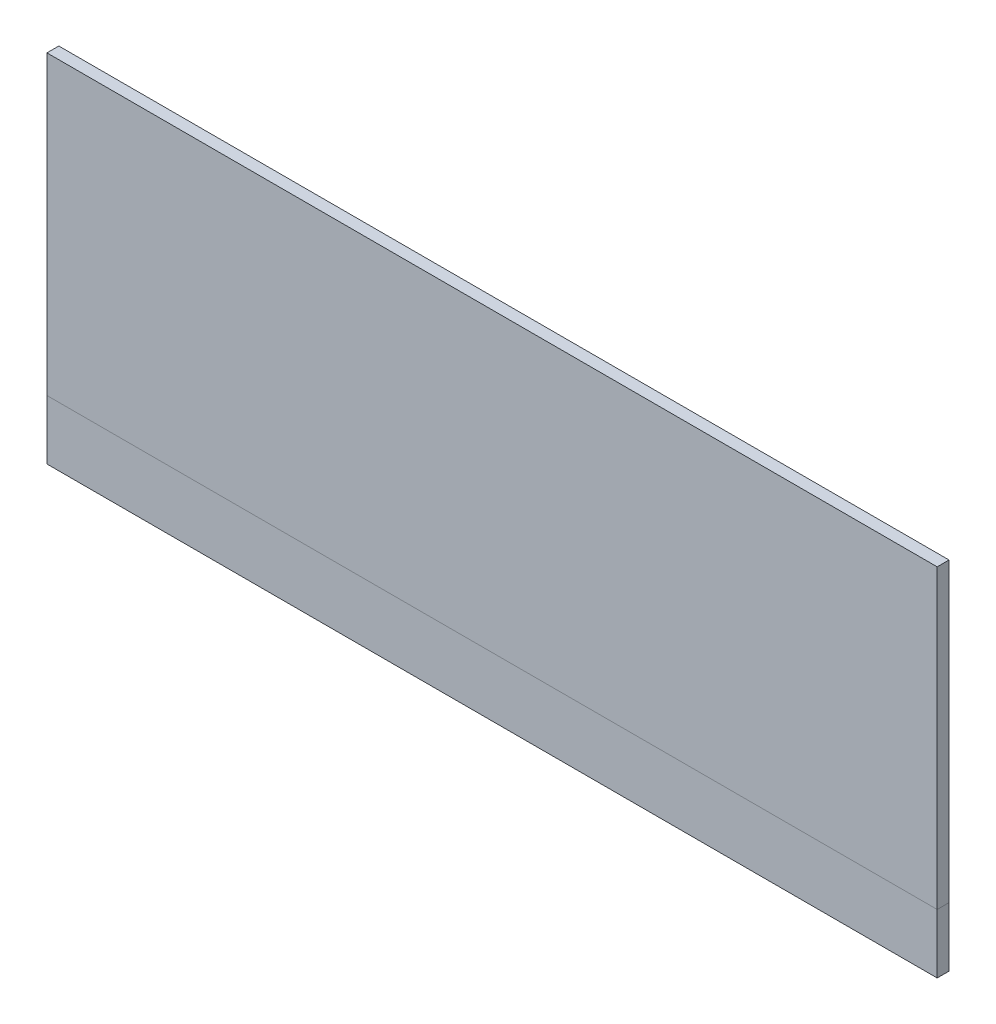
SolidWorks part; units mm, degrees
ref_plane "Front Plane" through (0, 0, 0) normal (0, 0, 1) x (1, 0, 0)
ref_plane "Top Plane" through (0, 0, 0) normal (0, 1, 0) x (1, 0, 0)
ref_plane "Right Plane" through (0, 0, 0) normal (1, 0, 0) x (0, 0, -1)
sketch "Sketch1" plane through (0, 0, 0) normal (0, 0, 1) x (1, 0, 0)
  line L1 (-187.5, 62.5) -> (187.5, 62.5)
  line L2 (-187.5, 62.5) -> (-187.5, -62.5)
  line L3 (-187.5, -62.5) -> (187.5, -62.5)
  line L4 (187.5, 62.5) -> (187.5, -62.5)
  line L5 (-187.5, 62.5) -> (187.5, -62.5) construction
  line L6 (-187.5, -62.5) -> (187.5, 62.5) construction
  point P0 (0, 0)
  dimension "D1" = 125
  dimension "D2" = 375
extrude "Boss-Extrude1" add sketch "Sketch1" along normal blind 5
sketch "Sketch2" plane through (0, 0, 5) normal (0, 0, 1) x (1, 0, 0)
  line L1 (-187.5, -62.5) -> (187.5, -62.5)
  line L2 (-187.5, -62.5) -> (-187.5, -87.5)
  line L3 (-187.5, -87.5) -> (187.5, -87.5)
  line L4 (187.5, -62.5) -> (187.5, -87.5)
  dimension "D1" = 25
extrude "Boss-Extrude2" add sketch "Sketch2" against normal blind 5 separate body
